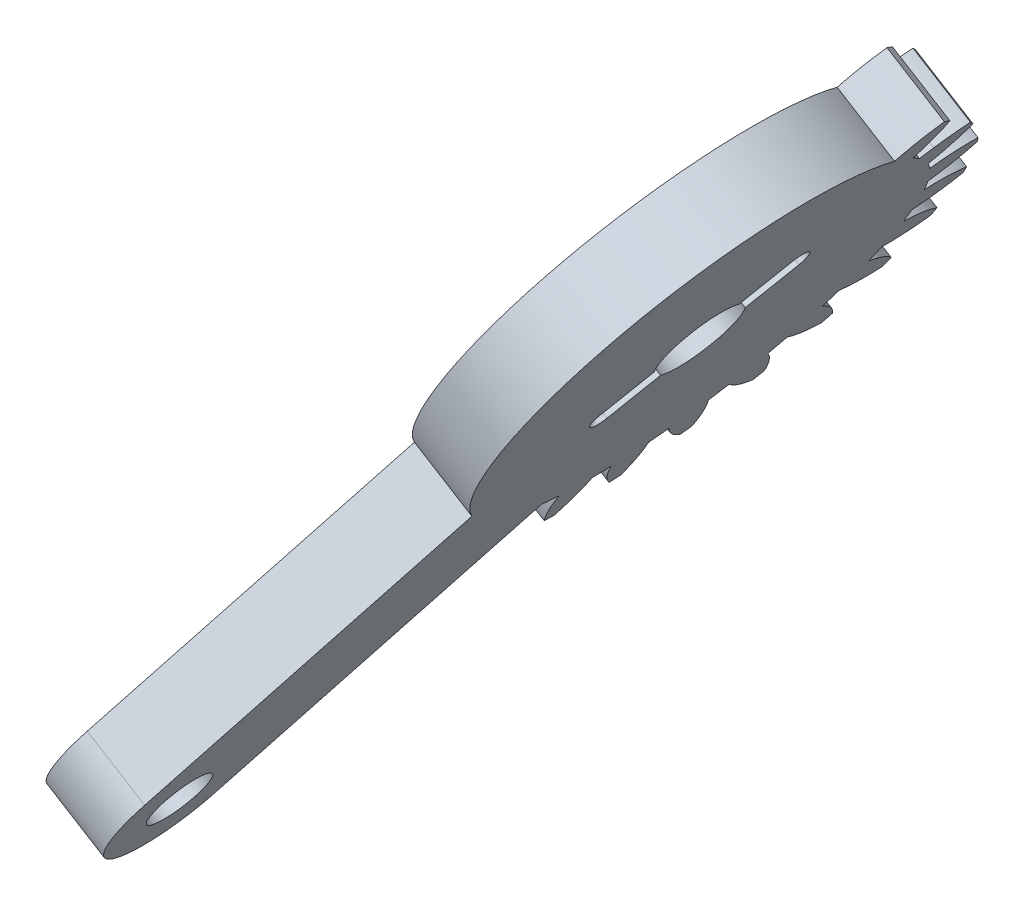
SolidWorks part; units mm, degrees
ref_plane "Front Plane" through (0, 0, 0) normal (0, 0, 1) x (1, 0, 0)
ref_plane "Top Plane" through (0, 0, 0) normal (0, 1, 0) x (1, 0, 0)
ref_plane "Right Plane" through (0, 0, 0) normal (1, 0, 0) x (0, 0, -1)
ref_plane "Plane1" through (-201.8493, 125.418, 0.5938) normal (0.8494, -0.5278, -0.0025) x (0.5278, 0.8494, 0)
sketch "Sketch1" plane through (-201.8493, 125.418, 0.5938) normal (0.8494, -0.5278, -0.0025) x (0.5278, 0.8494, 0)
  line L0 (162.2084, 97.8813) -> (161.8209, 98.5324)
  line L1 (146.1525, 116.8472) -> (130.2895, 127.9071)
  line L2 (125.7141, 121.3446) -> (141.5771, 110.2847)
  circle A0 centre (128.0018, 124.6259) radius 1.75
  circle A1 centre (153.2261, 107.0391) radius 2.4
  arc A4 (162.8859, 96.0582) -> (162.2084, 97.8813) centre (157.5681, 95.1195) ccw
  arc A5 (161.8209, 98.5324) -> (162.5151, 99.2964) centre (153.2261, 107.0391) ccw
  arc A6 (162.5151, 99.2964) -> (165.0418, 98.4205) centre (165.4919, 103.8017) ccw
  arc A7 (165.0418, 98.4205) -> (165.3988, 98.9325) centre (153.2261, 107.0391) ccw
  arc A8 (165.3988, 98.9325) -> (163.7033, 101.0006) centre (160.5052, 96.6494) ccw
  arc A9 (163.7033, 101.0006) -> (146.1525, 116.8472) centre (153.2261, 107.0391) ccw
  arc A10 (130.2895, 127.9071) -> (125.7141, 121.3446) centre (128.0018, 124.6259) ccw
  arc A11 (141.5771, 110.2847) -> (141.3103, 109.1) centre (153.2261, 107.0391) ccw
  arc A12 (141.3103, 109.1) -> (138.6841, 108.5951) centre (140.9849, 103.7098) ccw
  arc A13 (138.6841, 108.5951) -> (138.631, 107.9732) centre (153.2261, 107.0391) ccw
  arc A14 (138.631, 107.9732) -> (141.1334, 107.03) centre (141.7274, 112.3973) ccw
  arc A15 (141.1334, 107.03) -> (141.1829, 105.9457) centre (153.2261, 107.0391) ccw
  arc A16 (141.1829, 105.9457) -> (138.7769, 104.7783) centre (142.2637, 100.655) ccw
  arc A17 (138.7769, 104.7783) -> (138.8865, 104.1639) centre (153.2261, 107.0391) ccw
  arc A18 (138.8865, 104.1639) -> (141.5478, 103.9005) centre (140.7324, 109.2386) ccw
  arc A19 (141.5478, 103.9005) -> (141.8762, 102.8659) centre (153.2261, 107.0391) ccw
  arc A20 (141.8762, 102.8659) -> (139.8544, 101.1156) centre (144.2896, 98.0352) ccw
  arc A21 (139.8544, 101.1156) -> (140.1193, 100.5505) centre (153.2261, 107.0391) ccw
  arc A22 (140.1193, 100.5505) -> (142.758, 100.9849) centre (140.5888, 105.93) ccw
  arc A23 (142.758, 100.9849) -> (143.3431, 100.0706) centre (153.2261, 107.0391) ccw
  arc A24 (143.3431, 100.0706) -> (141.8431, 97.8566) centre (146.9245, 96.0291) ccw
  arc A25 (141.8431, 97.8566) -> (142.2453, 97.3793) centre (153.2261, 107.0391) ccw
  arc A26 (142.2453, 97.3793) -> (144.6817, 98.4818) centre (141.3065, 102.697) ccw
  arc A27 (144.6817, 98.4818) -> (145.4834, 97.7501) centre (153.2261, 107.0391) ccw
  arc A28 (145.4834, 97.7501) -> (144.6076, 95.2234) centre (149.9888, 94.7733) ccw
  arc A29 (144.6076, 95.2234) -> (145.1196, 94.8664) centre (153.2261, 107.0391) ccw
  arc A30 (145.1196, 94.8664) -> (147.1876, 96.5619) centre (142.8364, 99.76) ccw
  arc A31 (147.1876, 96.5619) -> (148.1514, 96.0627) centre (153.2261, 107.0391) ccw
  arc A32 (148.1514, 96.0627) -> (147.9594, 93.3953) centre (153.2737, 94.3533) ccw
  arc A33 (147.9594, 93.3953) -> (148.5463, 93.183) centre (153.2261, 107.0391) ccw
  arc A34 (148.5463, 93.183) -> (150.105, 95.356) centre (145.0744, 97.319) ccw
  arc A35 (150.105, 95.356) -> (151.1652, 95.1232) centre (153.2261, 107.0391) ccw
  arc A36 (151.1652, 95.1232) -> (151.6701, 92.4971) centre (156.5554, 94.7979) ccw
  arc A37 (151.6701, 92.4971) -> (152.292, 92.4439) centre (153.2261, 107.0391) ccw
  arc A38 (152.292, 92.4439) -> (153.2352, 94.9463) centre (147.8679, 95.5404) ccw
  arc A39 (153.2352, 94.9463) -> (154.3195, 94.9959) centre (153.2261, 107.0391) ccw
  arc A40 (154.3195, 94.9959) -> (155.4869, 92.5899) centre (159.6102, 96.0767) ccw
  arc A41 (155.4869, 92.5899) -> (156.1013, 92.6995) centre (153.2261, 107.0391) ccw
  arc A42 (156.1013, 92.6995) -> (156.3647, 95.3607) centre (151.0266, 94.5454) ccw
  arc A43 (156.3647, 95.3607) -> (157.3992, 95.6892) centre (153.2261, 107.0391) ccw
  arc A44 (157.3992, 95.6892) -> (159.1496, 93.6673) centre (162.23, 98.1026) ccw
  arc A45 (159.1496, 93.6673) -> (159.7147, 93.9323) centre (153.2261, 107.0391) ccw
  arc A46 (159.7147, 93.9323) -> (159.2803, 96.571) centre (154.3352, 94.4018) ccw
  arc A47 (159.2803, 96.571) -> (160.1946, 97.156) centre (153.2261, 107.0391) ccw
  arc A48 (160.1946, 97.156) -> (162.4086, 95.6561) centre (164.2361, 100.7374) ccw
  arc A49 (162.4086, 95.6561) -> (162.8859, 96.0582) centre (153.2261, 107.0391) ccw
extrude "Boss-Extrude1" add sketch "Sketch1" against normal blind 4
sketch "Sketch3" plane through (-201.8493, 125.418, 0.5938) normal (0.8494, -0.5278, -0.0025) x (-0.0021, 0.0013, -1)
  line L0 (-110.9678, 149.8625) -> (-103.1104, 156.5898) construction
  line L1 (-111.4556, 150.4322) -> (-103.5982, 157.1595)
  line L2 (-110.48, 149.2927) -> (-102.6226, 156.0201)
  arc A0 (-111.4556, 150.4322) -> (-110.48, 149.2927) centre (-110.9678, 149.8625) ccw
  arc A1 (-102.6226, 156.0201) -> (-103.5982, 157.1595) centre (-103.1104, 156.5898) ccw
  point P2 (-107.0391, 153.2261)
  dimension "D1" = 1.5
extrude "Cut-Extrude1" cut sketch "Sketch3" against normal blind 10
